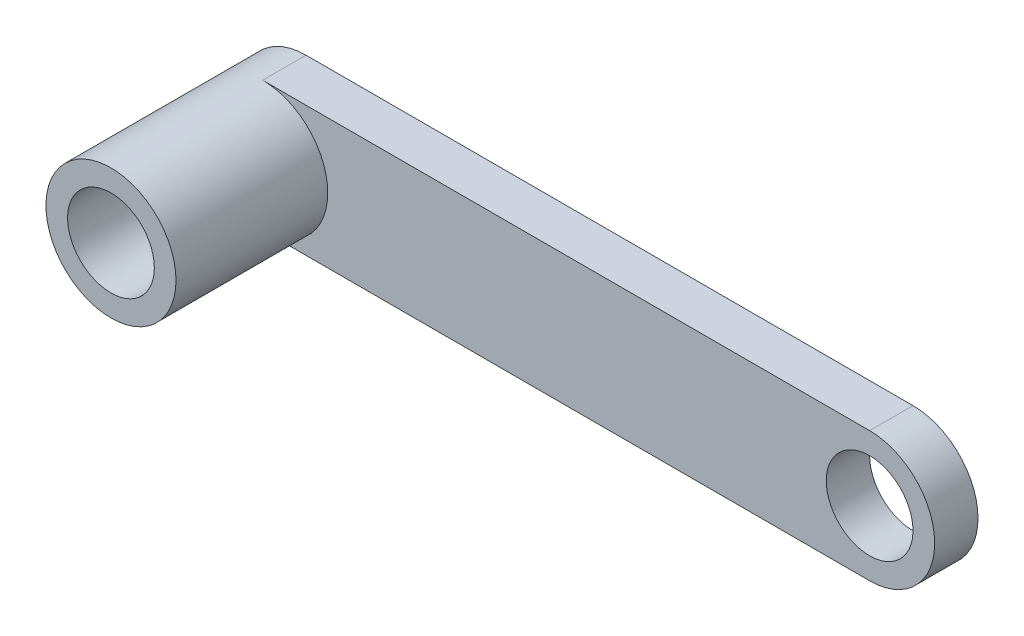
SolidWorks part; units mm, degrees
ref_plane "Alzado" through (0, 0, 0) normal (0, 0, 1) x (1, 0, 0)
ref_plane "Planta" through (0, 0, 0) normal (0, 1, 0) x (1, 0, 0)
ref_plane "Vista lateral" through (0, 0, 0) normal (1, 0, 0) x (0, 0, -1)
sketch "Croquis1" plane through (0, 0, 0) normal (0, 0, 1) x (1, 0, 0)
  line L4 (20.7075, 22.5) -> (20.7075, -7.5) construction
  line L5 (-49.2925, 22.5) -> (90.7075, 22.5)
  line L7 (-49.2925, -7.5) -> (90.7075, -7.5)
  arc A6 (-49.2925, 22.5) -> (-49.2925, -7.5) centre (-49.2925, 7.5) ccw
  circle A7 centre (-49.2925, 7.5) radius 10
  arc A8 (90.7075, 22.5) -> (90.7075, -7.5) centre (90.7075, 7.5) cw
  circle A9 centre (90.7075, 7.5) radius 10
  dimension "D3" = 140
  dimension "D1" = 20
  dimension "D2" = 30
extrude "Saliente-Extruir1" add sketch "Croquis1" along normal blind 10
sketch "Croquis2" plane through (0, 0, 10) normal (0, 0, 1) x (1, 0, 0)
  circle A0 centre (-49.2925, 7.5) radius 15
  circle A1 centre (-49.2925, 7.5) radius 10
  dimension "D1" = 20
extrude "Saliente-Extruir2" add sketch "Croquis2" along normal blind 35
sketch "Sketch1" plane through (0, 0, 45) normal (0, 0, 1) x (1, 0, 0)
  circle A0 centre (-49.2925, 7.5) radius 10
  circle A1 centre (-49.2925, 7.5) radius 15
